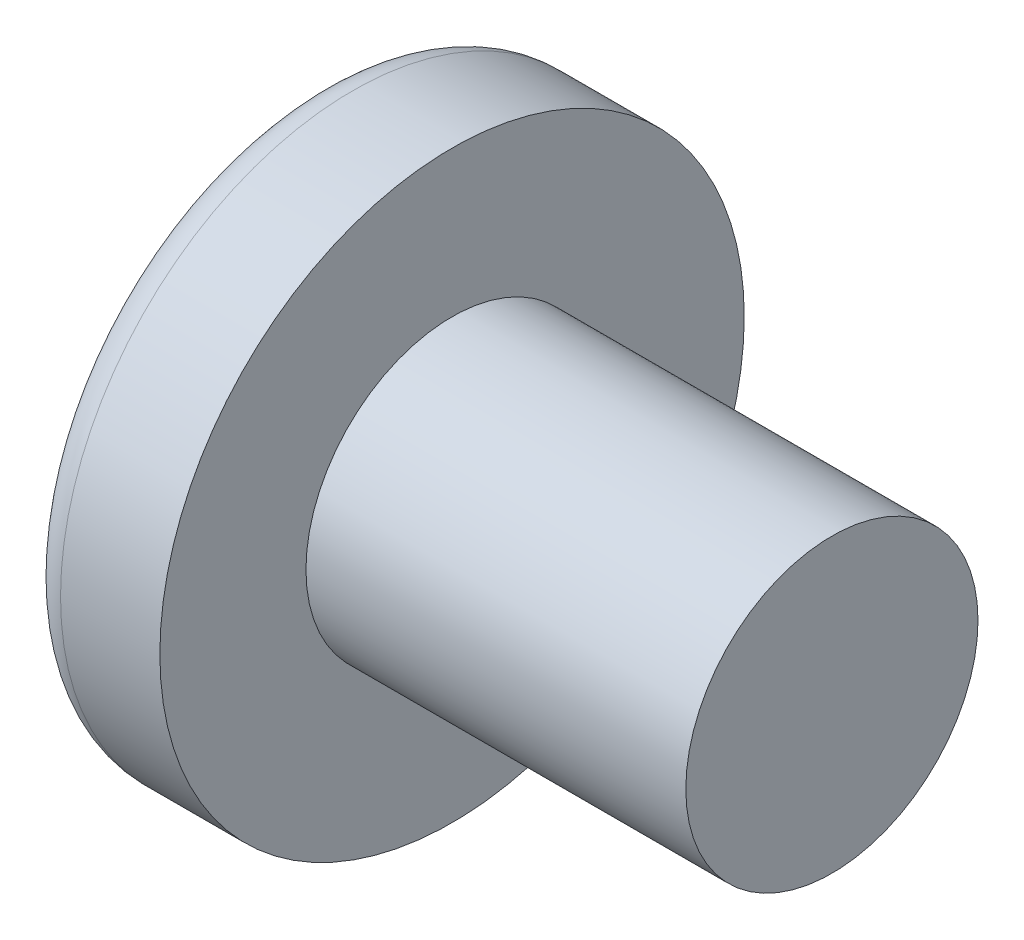
SolidWorks part; units mm, degrees
ref_plane "Plane1" through (0, 0, 0) normal (0, 0, 1) x (1, 0, 0)
ref_plane "Plane2" through (0, 0, 0) normal (0, 1, 0) x (1, 0, 0)
ref_plane "Plane3" through (0, 0, 0) normal (1, 0, 0) x (0, 0, -1)
sketch "BodySke" plane through (0, 0, 0) normal (0, 0, 1) x (1, 0, 0)
  line L0 (7.5, 5) -> (7.5, 10)
  line L1 (9, 6.35) -> (9, -3.175) construction
  line L2 (-25.4, 0) -> (127, 0) construction
  line L3 (20.5, 0) -> (0, 0)
  line L4 (7.5, 5) -> (20.5, 5)
  line L5 (20.5, 5) -> (20.5, 0)
  line L6 (4.1004, 10) -> (7.5, 10)
  line L7 (7.5, -5) -> (20.5, -5) construction
  line L8 (7.5, 6.35) -> (7.5, -3.175) construction
  arc A0 (3.1356, 9.5135) -> (0, 0) centre (16, 0) ccw
  arc A2 (3.1356, 9.5135) -> (4.1004, 10) centre (4.1004, 8.8) cw
revolve "Base-Revolve" add sketch "BodySke" angle 360 about L2
cosmetic thread "ThreadCosmetic" [suppressed] parameters "Thread_length"=5.6, "Thread_minor"=8.344
sketch "Sketch3" plane through (0, 0, 0) normal (1, 0, 0) x (0, 0, -1)
  line L0 (0.92, -5.09) -> (-0.92, -5.09)
  line L1 (0.92, -5.09) -> (0.92, 5.09)
  line L2 (-0.92, 5.09) -> (0.92, 5.09)
  line L3 (-0.92, 5.09) -> (-0.92, -5.09)
  dimension "D1" = 0.91
  dimension "D2" = 0.24
ref_plane "Plane4" through (6.09, 0, 0) normal (1, 0, 0) x (0, 0, -1)
sketch "Sketch4" plane through (6.09, 0, 0) normal (1, 0, 0) x (0, 0, -1)
  line L0 (0.46, -0.46) -> (-0.46, -0.46)
  line L1 (0.46, -0.46) -> (0.46, 0.46)
  line L2 (-0.46, 0.46) -> (0.46, 0.46)
  line L3 (-0.46, 0.46) -> (-0.46, -0.46)
  dimension "D2" = 0.24
  dimension "D1" = 0.24
  dimension "D3" = 0.12
  dimension "D4" = 0.12
loft "Cut-Loft1" cut profiles "Sketch3", "Sketch4"
pattern_circular "CirPattern1" count 2 every 90 about axis through (0, 0, 0) along (1, 0, 0) of "Cut-Loft1"
sketch "ThdSchSke" plane through (0, 0, 0) normal (0, 0, 1) x (1, 0, 0)
  line L0 (9, -4.172) -> (8.4202, -5)
  line L1 (9, -4.172) -> (9.5798, -5)
  line L2 (9.5798, -5) -> (9.5798, -6.25)
  line L3 (-3.175, 0) -> (5.1513, 0) construction
  line L5 (9.5798, -6.25) -> (8.4202, -6.25)
  line L6 (8.4202, -6.25) -> (8.4202, -5)
  dimension "SideAngle" = 55
  dimension "VeeAngle" = 70
  dimension "Thread_minor" = 1.548
  dimension "Overcut" = 2.5
  dimension "Diameter" = 2
  dimension "Start" = 2
revolve "ThreadSchematic" [suppressed] cut sketch "ThdSchSke" angle 360 about L3
pattern_linear "ThdSchPat" [suppressed]
equation "\"D1@Sketch3\" = \"Cross_dia@Sketch3\" / 2"
equation "\"D2@Sketch3\" = \"Cross_width@Sketch3\" / 2"
equation "\"D1@Sketch4\" = \"Cross_width@Sketch3\" *.5"
equation "\"D2@Sketch4\" = \"D1@Sketch4\""
equation "\"D3@Sketch4\" = \"D1@Sketch4\" / 2"
equation "\"D4@Sketch4\" = \"D2@Sketch4\" / 2"
equation "\"Thread_length@ThreadCosmetic\" = ((sgn( (\"Length@BodySke\" - \"Advance@BodySke\" ) - \"Thread_nom@BodySke\" )-1)*( (\"Length@BodySke\" - \"Advance@BodySke\" ) - \"Thread_nom@BodySke\" ))/-2+ \"Thread_nom@BodySke\""
equation "\"Thread_minor@ThdSchSke\" = \"Thread_minor@ThreadCosmetic\""
equation "\"Diameter@ThdSchSke\" = \"Diameter@BodySke\""
equation "\"Overcut@ThdSchSke\" = \"Diameter@BodySke\" * 1.25"
equation "\"Start@ThdSchSke\" = \"Head_ht@BodySke\" + \"Length@BodySke\" - \"Thread_length@ThreadCosmetic\"  '---Non-countersunk---"
equation "\"Num_threads@ThdSchPat\" = int( \"Thread_length@ThreadCosmetic\" / \"Advance@BodySke\" + 0.999 )  + 1"
equation "\"Advance@ThdSchPat\" = \"Thread_length@ThreadCosmetic\" /  (\"Num_threads@ThdSchPat\" - 1) 'relax it"
